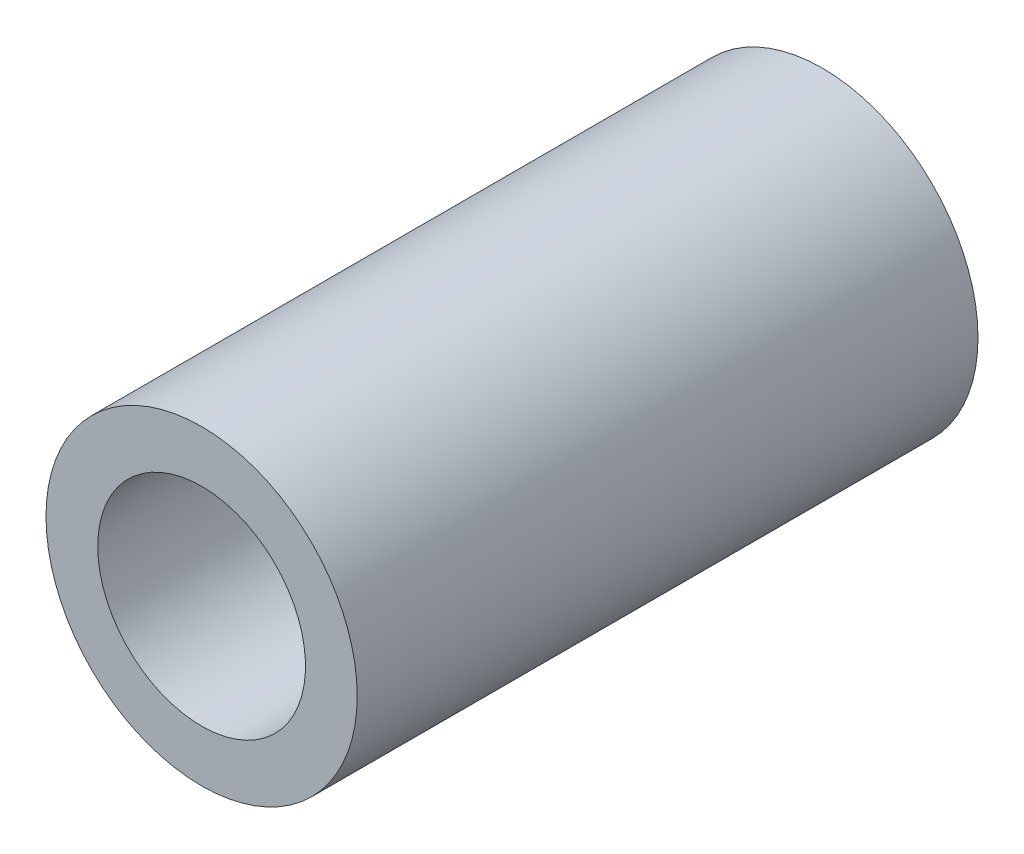
SolidWorks part; units mm, degrees
ref_plane "Front Plane" through (0, 0, 0) normal (0, 0, 1) x (1, 0, 0)
ref_plane "Top Plane" through (0, 0, 0) normal (0, 1, 0) x (1, 0, 0)
ref_plane "Right Plane" through (0, 0, 0) normal (1, 0, 0) x (0, 0, -1)
sketch "Sketch1" plane through (0, 0, 0) normal (0, 0, 1) x (1, 0, 0)
  circle A0 centre (0, 0) radius 9.5504
  circle A1 centre (0, 0) radius 6.3754
  dimension "D1" = 19.1008
  dimension "ID" = 12.7508
extrude "Extrude1" add sketch "Sketch1" along normal mid plane 38.1
sketch "Sketch2" plane through (0, 0, 0) normal (1, 0, 0) x (0, 0, -1)
  line L0 (-19.05, -6.3754) -> (19.05, -6.3754) construction
  line L3 (19.05, 6.3754) -> (-19.05, 6.3754) construction
  line L5 (-19.05, -6.3754) -> (19.05, -6.3754)
  line L6 (19.05, 6.3754) -> (-19.05, 6.3754)
sketch "Sketch4" plane through (0, 0, 19.05) normal (0, 0, 1) x (1, 0, 0)
  line L0 (0, 0) -> (-4.5081, 4.5081)
  line L1 (0, -3.4925) -> (0, 3.4925) construction
  circle A0 centre (0, 0) radius 6.3754 construction
  dimension "D1" = 45
